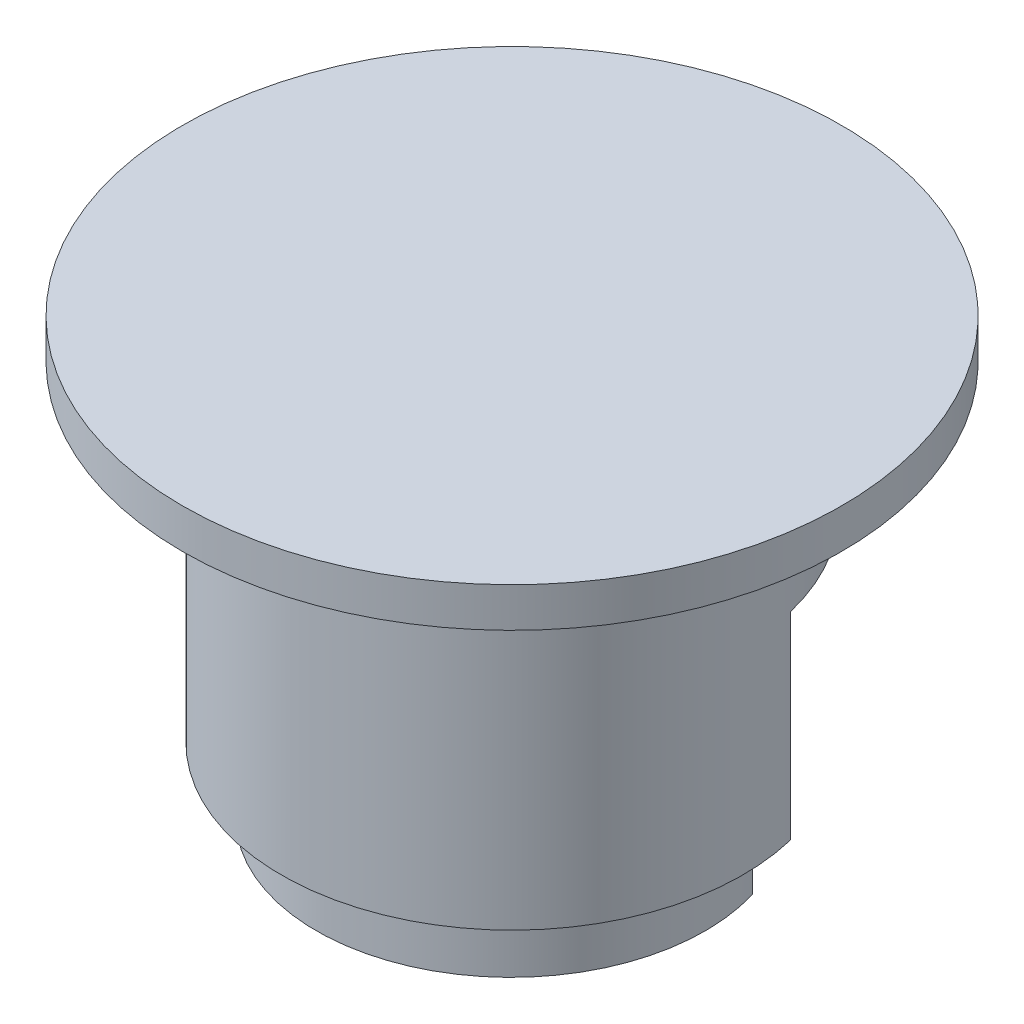
SolidWorks part; units mm, degrees
ref_plane "前视基准面" through (0, 0, 0) normal (0, 0, 1) x (1, 0, 0)
ref_plane "上视基准面" through (0, 0, 0) normal (0, 1, 0) x (1, 0, 0)
ref_plane "右视基准面" through (0, 0, 0) normal (1, 0, 0) x (0, 0, -1)
sketch "草图1" plane through (0, 0, 0) normal (0, 1, 0) x (1, 0, 0)
  circle A0 centre (0, 0) radius 50
  dimension "D1" = 100
extrude "凸台-拉伸1" add sketch "草图1" along normal blind 6
sketch "草图2" plane through (0, 0, 0) normal (0, -1, 0) x (1, 0, 0)
  circle A0 centre (0, 0) radius 35
  dimension "D1" = 70
extrude "凸台-拉伸2" add sketch "草图2" along normal blind 60
sketch "草图3" plane through (0, -60, 0) normal (0, -1, 0) x (1, 0, 0)
  circle A0 centre (0, 0) radius 27.5
  dimension "D1" = 55
sketch "草图4" plane through (0, -60, 0) normal (0, -1, 0) x (1, 0, 0)
  line L1 (-36.6948, -8.2073) -> (40.7539, -8.2073)
  line L2 (-36.6948, -8.2073) -> (-36.6948, -41.2073)
  line L3 (-36.6948, -41.2073) -> (40.7539, -41.2073)
  line L4 (40.7539, -8.2073) -> (40.7539, -41.2073)
  dimension "D1" = 33
extrude "切除-拉伸2" cut sketch "草图4" against normal blind 40
sketch "草图5" plane through (0, 0, -8.2073) normal (0, 0, -1) x (-1, 0, 0)
  line L0 (0, -20) -> (0, -123.4078) construction
  line L1 (-34.0241, -20) -> (34.0241, -20) construction
  line L2 (-34.0241, -20) -> (34.0241, -20) construction
  line L3 (-6, -65) -> (6, -65)
  line L4 (-6, -65) -> (-6, -20)
  line L5 (-6, -20) -> (6, -20)
  line L6 (6, -65) -> (6, -20)
  line L7 (0, -20) -> (0, -65) construction
  line L8 (-6, -42.5) -> (6, -42.5) construction
  point P5 (0, -42.5)
  dimension "D1" = 12
  dimension "D2" = 45
extrude "切除-拉伸3" cut sketch "草图5" against normal blind 30
sketch "草图6" plane through (0, -60, 0) normal (0, -1, 0) x (1, 0, 0)
  line L0 (-27.5, 0) -> (-25.6518, -3.4188)
  line L1 (-25.6518, -3.4188) -> (25.982, -3.4188)
  line L2 (27.5, 0) -> (25.982, -3.4188)
  circle A1 centre (0, 0) radius 27.5 construction
  arc A2 (-27.5, 0) -> (27.5, 0) centre (0, 0) cw
  point P6 (26.042, -3.2837)
  point P8 (-25.6518, -3.4188)
  dimension "D1" = 27.5
extrude "切除-拉伸4" cut sketch "草图6" along direction (0, 1, 0) on the side against the normal blind 60 and the other way through all
sketch "草图7" plane through (0, -60, 0) normal (0, -1, 0) x (1, 0, 0)
  circle A0 centre (0, 0.1843) radius 29.5
  dimension "D1" = 59
extrude "切除-拉伸5" cut sketch "草图7" against normal blind 10 flip side to cut
sketch "草图8" plane through (0, -20, 0) normal (0, -1, 0) x (1, 0, 0)
  line L0 (-29.3841, -11.494) -> (28.6159, -11.494)
  arc A0 (-29.3841, -11.494) -> (28.6159, -11.494) centre (-0.3841, -0.3978) ccw
  dimension "D2" = 58
extrude "切除-拉伸6" cut sketch "草图8" against normal blind 20
sketch "草图9" plane through (0, 0, -8.2073) normal (0, 0, -1) x (-1, 0, 0)
  line L0 (0, -52.6874) -> (0, -21.7685) construction
  circle A0 centre (21.25, -28.1403) radius 1.1
  circle A1 centre (21.25, -44.4403) radius 1.1
  circle A2 centre (-21.25, -28.1403) radius 1.1
  circle A3 centre (-21.25, -44.4403) radius 1.1
  point P4 (21.25, -28.1403)
  dimension "D1" = 2.2
  dimension "D2" = 42.5
  dimension "D3" = 42.5
  dimension "D4" = 16.3
extrude "切除-拉伸7" cut sketch "草图9" against normal blind 10
fillet "圆角1" radius 2 4 edges at (-25.6518, -30, -3.4188) (-27.5, -30, 0) (25.982, -30, -3.4188) (27.5, -30, 0)
